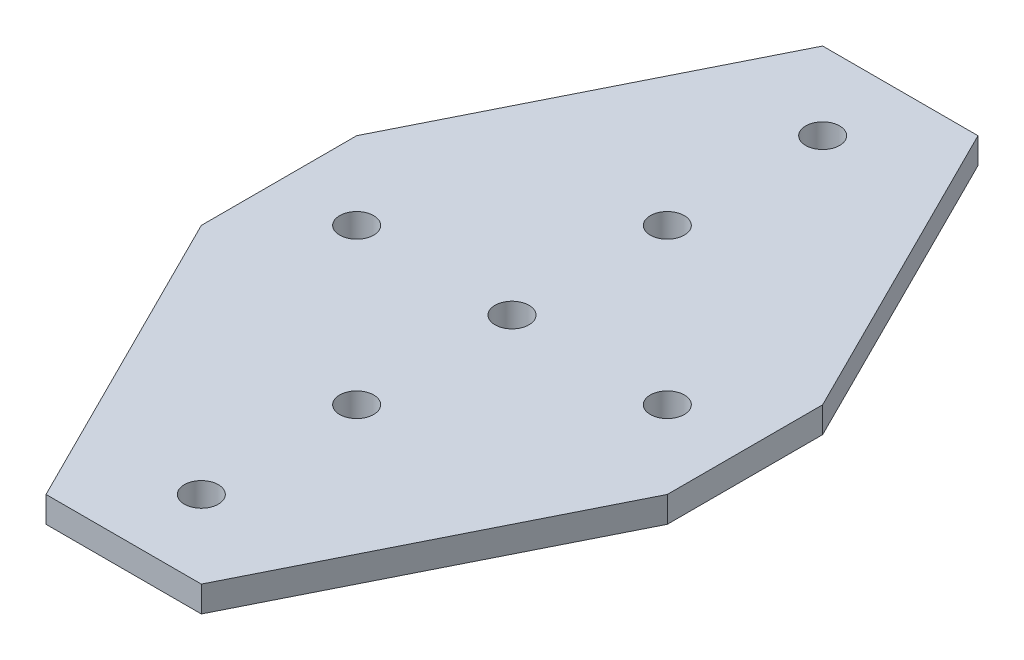
SolidWorks part; units mm, degrees
ref_plane "Front Plane" through (0, 0, 0) normal (0, 0, 1) x (1, 0, 0)
ref_plane "Top Plane" through (0, 0, 0) normal (0, 1, 0) x (1, 0, 0)
ref_plane "Right Plane" through (0, 0, 0) normal (1, 0, 0) x (0, 0, -1)
sketch "Sketch1" plane through (0, 0, 0) normal (0, 1, 0) x (1, 0, 0)
  line L0 (-73.1004, 81.9103) -> (-35.0004, 81.9103)
  line L1 (-35.0004, 81.9103) -> (3.0996, 5.7103)
  line L2 (3.0996, 5.7103) -> (3.0996, -32.3897)
  line L3 (3.0996, -32.3897) -> (-35.0004, -108.5897)
  line L4 (-35.0004, -108.5897) -> (-73.1004, -108.5897)
  line L5 (-73.1004, -108.5897) -> (-111.2004, -32.3897)
  line L6 (-111.2004, -32.3897) -> (-111.2004, 5.7103)
  line L7 (-111.2004, 5.7103) -> (-73.1004, 81.9103)
  circle A0 centre (-92.1504, -13.3397) radius 4.1656
  circle A1 centre (-54.0504, -13.3397) radius 4.1656
  circle A2 centre (-15.9504, -13.3397) radius 4.1656
  circle A3 centre (-54.0504, 24.7603) radius 4.1656
  circle A4 centre (-54.0504, 62.8603) radius 4.1656
  circle A5 centre (-54.0504, -51.4397) radius 4.1656
  circle A6 centre (-54.0504, -89.5397) radius 4.1656
  dimension "D11" = 19.05
  dimension "D1" = 190.5
  dimension "D2" = 38.1
  dimension "D3" = 38.1
  dimension "D4" = 38.1
  dimension "D5" = 38.1
  dimension "D6" = 76.2
  dimension "D7" = 76.2
  dimension "D8" = 38.1
  dimension "D9" = 38.1
  dimension "D10" = 114.3
  dimension "D12" = 95.25
  dimension "D13" = 3
  dimension "D14" = 3
  dimension "D15" = 3
extrude "Boss-Extrude1" add sketch "Sketch1" along normal blind 6.35
